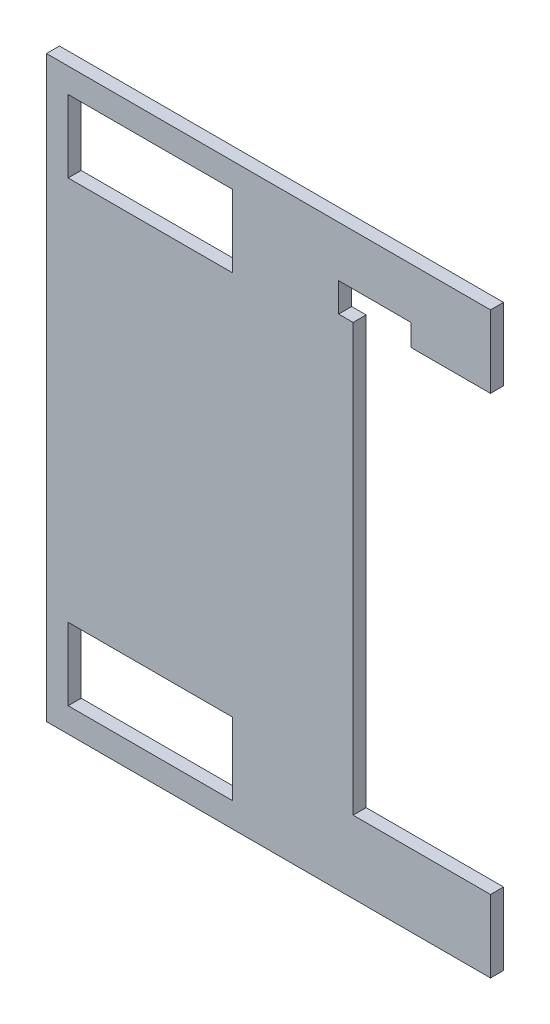
SolidWorks part; units mm, degrees
material "Pine"
ref_plane "Front Plane" through (0, 0, 0) normal (0, 0, 1) x (1, 0, 0)
ref_plane "Top Plane" through (0, 0, 0) normal (0, 1, 0) x (1, 0, 0)
ref_plane "Right Plane" through (0, 0, 0) normal (1, 0, 0) x (0, 0, -1)
sketch "Sketch1" plane through (0, 0, 0) normal (0, 0, 1) x (1, 0, 0)
  line L0 (-16.8129, -74.6) -> (-16.8129, 325.4)
  line L1 (-16.8129, 325.4) -> (-323.8122, 325.4)
  line L2 (-323.8122, 325.4) -> (-323.8122, -74.6)
  line L3 (-323.8122, -74.6) -> (-16.8129, -74.6)
  line L9 (-308.8122, 308.4) -> (-195.1729, 308.4)
  line L10 (-308.8122, 308.4) -> (-308.8122, 258.4)
  line L11 (-308.8122, 258.4) -> (-195.1729, 258.4)
  line L12 (-195.1729, 308.4) -> (-195.1729, 258.4)
  line L13 (-308.8122, 308.4) -> (-195.1729, 258.4) construction
  line L14 (-308.8122, 258.4) -> (-195.1729, 308.4) construction
  line L18 (-308.8122, -57.6) -> (-195.1729, -57.6)
  line L19 (-308.8122, -57.6) -> (-308.8122, -7.6)
  line L20 (-308.8122, -7.6) -> (-195.1729, -7.6)
  line L21 (-195.1729, -57.6) -> (-195.1729, -7.6)
  line L22 (-308.8122, -57.6) -> (-195.1729, -7.6) construction
  line L23 (-308.8122, -7.6) -> (-195.1729, -57.6) construction
  point P16 (-251.9926, 283.4)
  point P27 (-251.9926, -32.6)
  dimension "D2" = 50
  dimension "D3" = 17
  dimension "D5" = 15
  dimension "D6" = 15
extrude "Boss-Extrude1" add sketch "Sketch1" along normal blind 9
sketch "Sketch2" plane through (0, 0, 0) normal (0, 0, -1) x (-1, 0, 0)
  line L0 (111.8129, -24.6) -> (111.8129, 275.4)
  line L1 (16.8129, 325.4) -> (111.8129, 325.4)
  line L2 (16.8129, 325.4) -> (16.8129, 275.4)
  line L3 (16.8129, 275.4) -> (111.8129, 275.4)
  line L4 (111.8129, 325.4) -> (111.8129, 275.4)
  line L5 (16.8129, 325.4) -> (111.8129, 275.4) construction
  line L6 (16.8129, 275.4) -> (111.8129, 325.4) construction
  line L7 (16.8129, -74.6) -> (111.8129, -74.6)
  line L8 (16.8129, -74.6) -> (16.8129, -24.6)
  line L9 (16.8129, -24.6) -> (111.8129, -24.6)
  line L10 (111.8129, -74.6) -> (111.8129, -24.6)
  line L11 (16.8129, -74.6) -> (111.8129, -24.6) construction
  line L12 (16.8129, -24.6) -> (111.8129, -74.6) construction
  point P4 (64.3129, 300.4)
  point P10 (64.3129, -49.6)
  line M11 (16.8129, 325.4) -> (16.8129, -74.6)
  dimension "D1" = 50
  dimension "D2" = 50
  dimension "D3" = 95
extrude "Cut-Extrude1" cut sketch "Sketch2" against normal through all contours L9 L0 L3 M11
sketch "Sketch3" plane through (0, 0, 0) normal (0, 0, -1) x (-1, 0, 0)
  line L1 (111.8129, 275.4) -> (71.8129, 275.4)
  line L2 (111.8129, 275.4) -> (111.8129, 290.4)
  line L3 (111.8129, 290.4) -> (71.8129, 290.4)
  line L4 (71.8129, 275.4) -> (71.8129, 290.4)
  dimension "D1" = 40
  dimension "D2" = 15
extrude "Cut-Extrude2" cut sketch "Sketch3" against normal blind 10
sketch "Sketch4" plane through (0, 0, 0) normal (0, 0, -1) x (-1, 0, 0)
  line L1 (111.8129, 290.4) -> (121.8129, 290.4)
  line L2 (111.8129, 290.4) -> (111.8129, 270.4)
  line L3 (111.8129, 270.4) -> (121.8129, 270.4)
  line L4 (121.8129, 290.4) -> (121.8129, 270.4)
  dimension "D1" = 10
  dimension "D2" = 20
extrude "Cut-Extrude3" cut sketch "Sketch4" against normal blind 100
